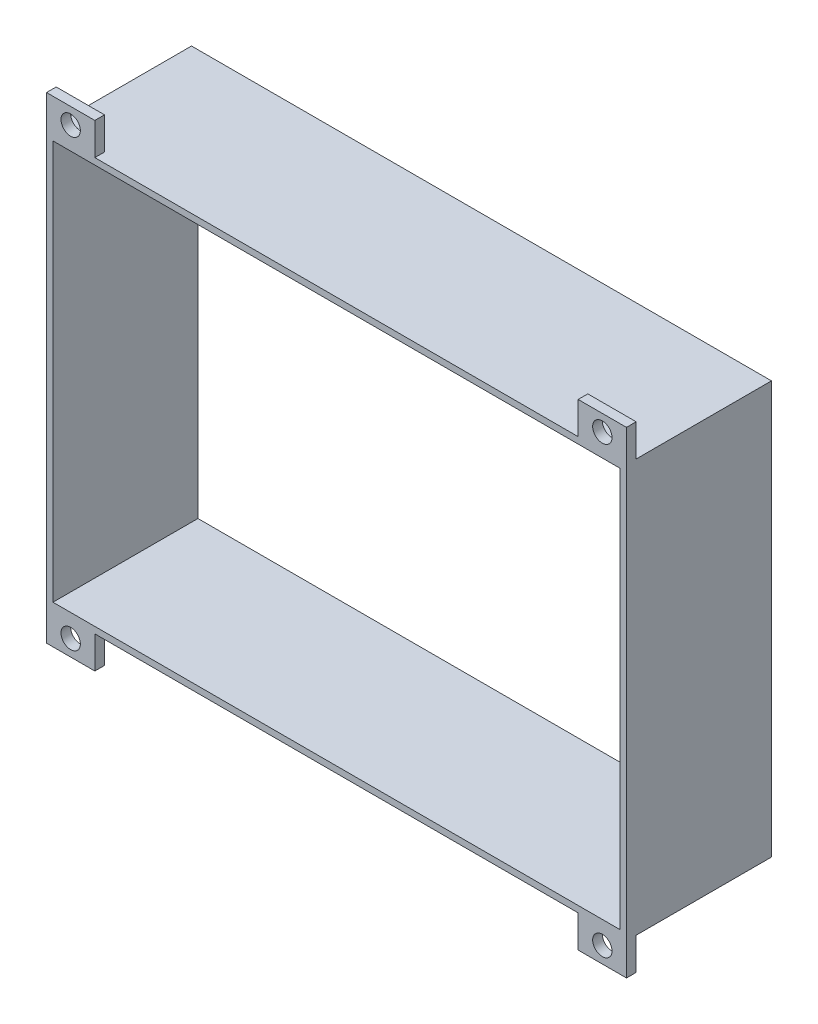
SolidWorks part; units mm, degrees
ref_plane "前基準面" through (0, 0, 0) normal (0, 0, 1) x (1, 0, 0)
ref_plane "上基準面" through (0, 0, 0) normal (0, 1, 0) x (1, 0, 0)
ref_plane "右基準面" through (0, 0, 0) normal (1, 0, 0) x (0, 0, -1)
sketch "草圖1" plane through (0, 0, 0) normal (0, 0, 1) x (1, 0, 0)
  line L1 (-90, 64) -> (90, 64)
  line L2 (-90, 64) -> (-90, -64)
  line L3 (-90, -64) -> (90, -64)
  line L4 (90, 64) -> (90, -64)
  line L5 (-90, 64) -> (90, -64) construction
  line L6 (-90, -64) -> (90, 64) construction
  line L7 (-88, 62) -> (88, 62)
  line L8 (-88, 62) -> (-88, -62)
  line L9 (-88, -62) -> (88, -62)
  line L10 (88, 62) -> (88, -62)
  line L11 (-88, 62) -> (88, -62) construction
  line L12 (-88, -62) -> (88, 62) construction
  point P0 (0, 0)
  point P6 (0, 0)
  dimension "D1" = 128
  dimension "D2" = 180
  dimension "D3" = 124
  dimension "D4" = 176
extrude "填料-伸長1" add sketch "草圖1" along normal blind 45
sketch "草圖2" plane through (0, -64, 0) normal (0, -1, 0) x (1, 0, 0)
  line L1 (90, 45) -> (75, 45)
  line L2 (90, 45) -> (90, 42)
  line L3 (90, 42) -> (75, 42)
  line L4 (75, 45) -> (75, 42)
  line L5 (-90, 45) -> (-75, 45)
  line L6 (-90, 45) -> (-90, 42)
  line L7 (-90, 42) -> (-75, 42)
  line L8 (-75, 45) -> (-75, 42)
  dimension "D1" = 3
  dimension "D2" = 3
  dimension "D3" = 15
  dimension "D4" = 15
extrude "填料-伸長2" add sketch "草圖2" along normal blind 10
sketch "草圖3" plane through (0, 0, 42) normal (0, 0, -1) x (-1, 0, 0)
  line L0 (-90, -74) -> (-90, -64) construction
  line L1 (90, -64) -> (-90, -64) construction
  line L2 (90, -74) -> (90, -64) construction
  line L3 (90, -64) -> (75, -64) construction
  circle A0 centre (-82.5, -69) radius 3
  circle A1 centre (82.5, -69) radius 3
  dimension "D1" = 6
  dimension "D2" = 6
  dimension "D3" = 7.5
  dimension "D4" = 5
  dimension "D5" = 7.5
  dimension "D6" = 5
extrude "除料-伸長1" cut sketch "草圖3" against normal blind 10
mirror "鏡射1" about plane through (0, 0, 0) normal (0, 1, 0) of "填料-伸長2"
mirror "鏡射3" about plane through (0, 0, 0) normal (0, 1, 0) of "除料-伸長1"
